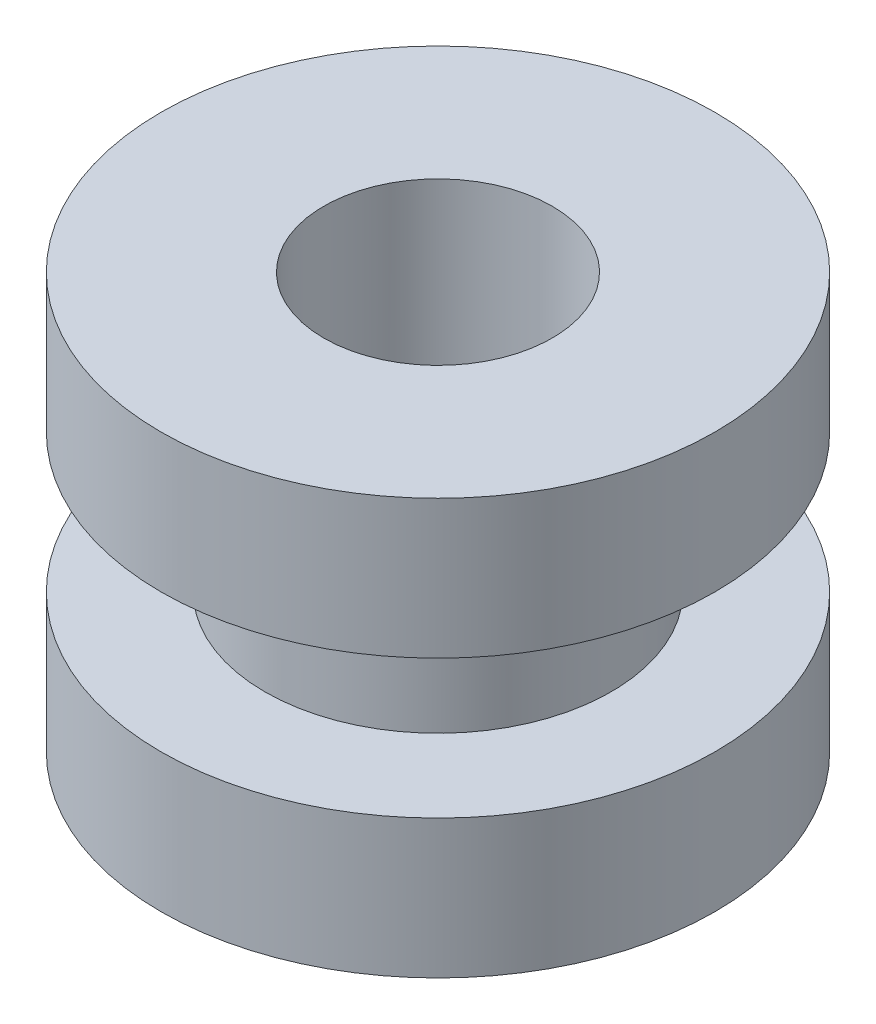
SolidWorks part; units mm, degrees
ref_plane "Front Plane" through (0, 0, 0) normal (0, 0, 1) x (1, 0, 0)
ref_plane "Top Plane" through (0, 0, 0) normal (0, 1, 0) x (1, 0, 0)
ref_plane "Right Plane" through (0, 0, 0) normal (1, 0, 0) x (0, 0, -1)
sketch "Sketch1" plane through (0, 0, 0) normal (0, 0, 1) x (1, 0, 0)
  line L0 (0, 0) -> (0, -6)
  line L1 (0, -6) -> (-8, -6)
  line L2 (-8, -6) -> (-8, -2)
  line L3 (-8, -2) -> (-5, -2)
  line L4 (-5, -2) -> (-5, 0)
  line L5 (-5, 0) -> (0, 0)
  dimension "D1" = 6
  dimension "D2" = 5
  dimension "D3" = 4
  dimension "D4" = 8
revolve "Revolve1" add sketch "Sketch1" angle 360 about L0
mirror "Mirror1" about plane through (-5, 0, 0) normal (0, 1, 0) of bodies 101
hole_wizard "CSK for M6 Flat Head Machine Screw1" positions "Sketch2" profile "Sketch3" countersink size "M6" standard "ANSI Metric" end condition up to next
sketch "Sketch2" plane through (0, -6, 0) normal (0, -1, 0) x (-1, 0, 0)
  point P0 (0, 0)
sketch "Sketch3" plane through (0, -6, 0) normal (1, 0, 0) x (0, 0, -1)
  line L0 (0, 0) -> (0, 12)
  line L1 (0, 12) -> (3.3, 12)
  line L2 (3.3, 12) -> (3.3, 3)
  line L3 (3.3, 3) -> (6.3, 0)
  line L5 (6.3, 0) -> (0, 0)
  line L6 (-3.3, 3) -> (-6.3, 0) construction
  line L11 (0, -6.35) -> (0, 107.95) construction
  dimension "Thru Hole Dia." = 6.6
  dimension "Thru Hole Depth" = 12
  dimension "Near C'Sink Dia." = 12.6
  dimension "Near C'Sink Angle" = 90
